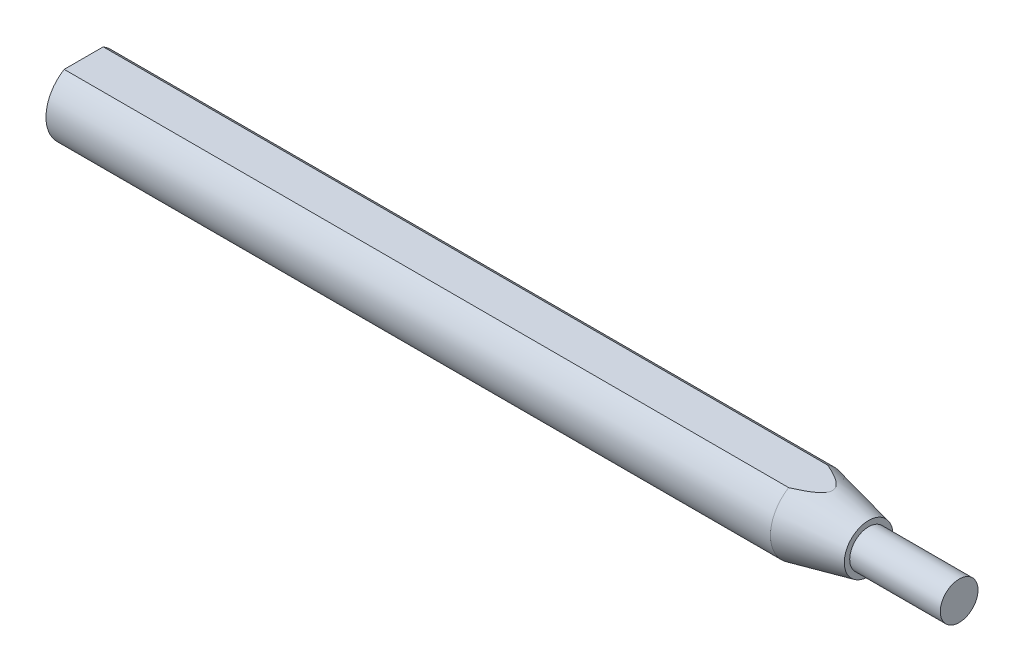
SolidWorks part; units mm, degrees
ref_plane "Front Plane" through (0, 0, 0) normal (0, 0, 1) x (1, 0, 0)
ref_plane "Top Plane" through (0, 0, 0) normal (0, 1, 0) x (1, 0, 0)
ref_plane "Right Plane" through (0, 0, 0) normal (1, 0, 0) x (0, 0, -1)
sketch "Sketch1" plane through (0, 0, 0) normal (1, 0, 0) x (0, 0, -1)
  circle A0 centre (0, 0) radius 3.175
  dimension "D1" = 6.35
extrude "Boss-Extrude1" add sketch "Sketch1" along normal blind 60.96
sketch "Sketch2" plane through (60.96, 0, 0) normal (1, 0, 0) x (0, 0, -1)
  circle A0 centre (0, 0) radius 1.5875
  dimension "D1" = 3.175
extrude "Boss-Extrude2" add sketch "Sketch2" along normal blind 12.7
sketch "Sketch4" plane through (0, 0, 0) normal (0, 0, 1) x (1, 0, 0)
  line L0 (60.96, -1.5875) -> (66.04, -1.5875)
  line L1 (60.96, -1.5875) -> (73.66, -1.5875) construction
  line L2 (66.04, -1.5875) -> (66.04, -2.0447)
  line L3 (66.04, -2.0447) -> (60.96, -3.175)
  line L4 (60.96, -3.175) -> (60.96, 3.175) construction
  line L5 (60.96, -3.175) -> (60.96, -1.5875)
  line L6 (60.96, 0) -> (66.04, 0) construction
  line L7 (60.96, -1.5875) -> (60.96, 1.5875) construction
  point P11 (60.96, -3.5168)
  point P12 (60.96, -2.907)
  dimension "D1" = 5.08
  dimension "D2" = 0.4572
revolve "Revolve1" add sketch "Sketch4" angle 360 about L6
sketch "Sketch3" plane through (0, 0, 0) normal (-1, 0, 0) x (0, 0, 1)
  line L0 (1.6414, 2.7178) -> (-1.6414, 2.7178)
  circle A0 centre (0, 0) radius 3.175 construction
  arc A1 (-1.6414, 2.7178) -> (1.6414, 2.7178) centre (0, 0) cw
  dimension "D1" = 2.7178
extrude "Cut-Extrude1" cut sketch "Sketch3" against normal through all
